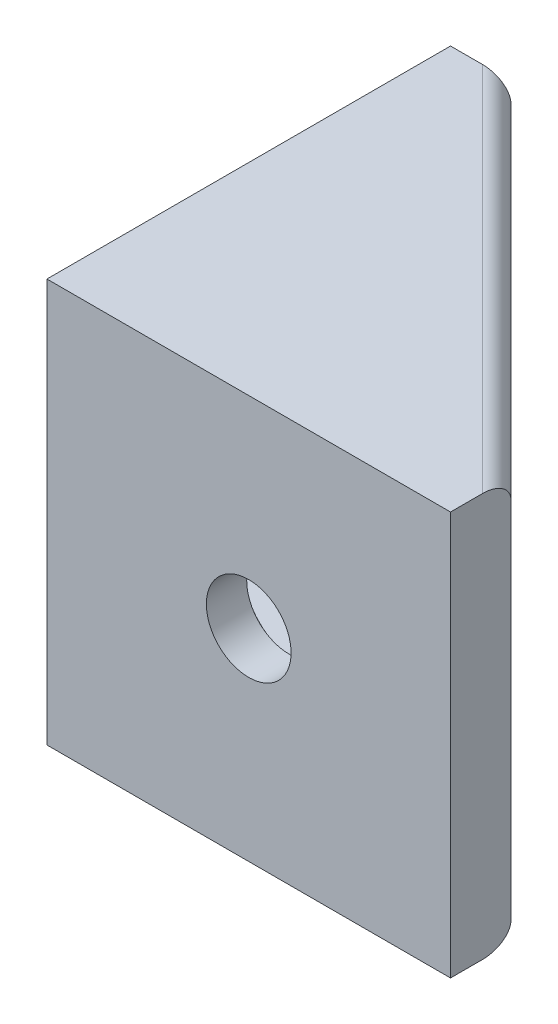
SolidWorks part; units mm, degrees
ref_plane "前视基准面" through (0, 0, 0) normal (0, 0, 1) x (1, 0, 0)
ref_plane "上视基准面" through (0, 0, 0) normal (0, 1, 0) x (1, 0, 0)
ref_plane "右视基准面" through (0, 0, 0) normal (1, 0, 0) x (0, 0, -1)
other "Configuration Table"
sketch "草图1" plane through (0, 0, 0) normal (0, 1, 0) x (1, 0, 0)
  line L0 (0, 20) -> (0, 0)
  line L1 (0, 0) -> (20, 0)
  line L2 (20, 0) -> (20, 3)
  line L3 (20, 3) -> (3, 3)
  line L4 (3, 3) -> (3, 20)
  line L5 (3, 20) -> (0, 20)
  dimension "D1" = 3
  dimension "D2" = 20
  dimension "D3" = 20
  dimension "D4" = 3
extrude "凸台-拉伸1" add sketch "草图1" along normal blind 20
sketch "草图2" plane through (0, 20, 0) normal (0, 1, 0) x (1, 0, 0)
  line L0 (3, 20) -> (20, 3)
  line L1 (20, 3) -> (3, 3)
  line L2 (3, 3) -> (3, 20)
extrude "凸台-拉伸2" add sketch "草图2" against normal blind 3
sketch "草图3" plane through (0, 0, 0) normal (0, -1, 0) x (1, 0, 0)
  line L0 (20, -3) -> (3, -20)
  line L1 (3, -20) -> (3, -3)
  line L2 (3, -3) -> (3, -20) construction
  line L3 (3, -20) -> (3, -3) construction
  line L4 (3, -3) -> (20, -3)
extrude "凸台-拉伸3" add sketch "草图3" against normal blind 3
chamfer "倒角1" distance 10 angle 45 1 edges at (3, 10, -3)
sketch "草图4" plane through (0, 0, -3) normal (0, 0, -1) x (-1, 0, 0)
  line L0 (-20, 20) -> (-3, 20) construction
  line L1 (-20, 17) -> (-20, 3) construction
  circle A0 centre (-10, 10) radius 2.1
  dimension "D3" = 4.2
  dimension "D1" = 10
  dimension "D2" = 10
extrude "切除-拉伸1" cut sketch "草图4" against normal blind 3
sketch "草图5" plane through (0, 0, -3) normal (0, 0, -1) x (-1, 0, 0)
  line L0 (-10, 13.5) -> (-13, 13.5)
  line L1 (-10, 6.5) -> (-13, 6.5)
  line L2 (-13, 13.5) -> (-13, 6.5)
  arc A0 (-10, 6.5) -> (-10, 13.5) centre (-10, 10) ccw
  dimension "D1" = 7
extrude "切除-拉伸2" cut sketch "草图5" along normal blind 10 contours A0 L0 L2 L1
fillet "圆角1" radius 1 2 edges at (11.5, 20, -11.5) (11.5, 0, -11.5)
sketch "草图6" plane through (3, 0, 0) normal (1, 0, 0) x (0, 0, -1)
  line L0 (1.5858, 20) -> (20, 20) construction
  line L1 (20, 17) -> (20, 3) construction
  circle A0 centre (10, 10) radius 2.1
  dimension "D3" = 4.2
  dimension "D1" = 10
  dimension "D2" = 10
extrude "切除-拉伸3" cut sketch "草图6" against normal blind 10
sketch "草图7" plane through (3, 0, 0) normal (-1, 0, 0) x (0, 0, 1)
  circle A0 centre (-10, 10) radius 3.5
  dimension "D1" = 7
extrude "切除-拉伸4" cut sketch "草图7" against normal blind 10
sketch "草图8" plane through (0, 13.5, 0) normal (0, -1, 0) x (1, 0, 0)
  line L1 (3, -13) -> (13, -13)
  line L2 (3, -13) -> (3, -3)
  line L3 (3, -3) -> (13, -3)
  line L4 (13, -13) -> (13, -3)
extrude "切除-拉伸5" cut sketch "草图8" along normal blind 7
fillet "圆角2" radius 1 4 edges at (8, 17, -8) (8, 3, -8) (8, 13.5, -8) (8, 6.5, -8)
sketch "草图9" plane through (0, 0, -3) normal (0, 0, -1) x (-1, 0, 0)
  circle A0 centre (-10, 10) radius 3.5
extrude "切除-拉伸6" cut sketch "草图9" against normal blind 1
sketch "草图10" plane through (3, 0, 0) normal (1, 0, 0) x (0, 0, -1)
  circle A0 centre (10, 10) radius 3.5
extrude "切除-拉伸7" cut sketch "草图10" against normal blind 1
